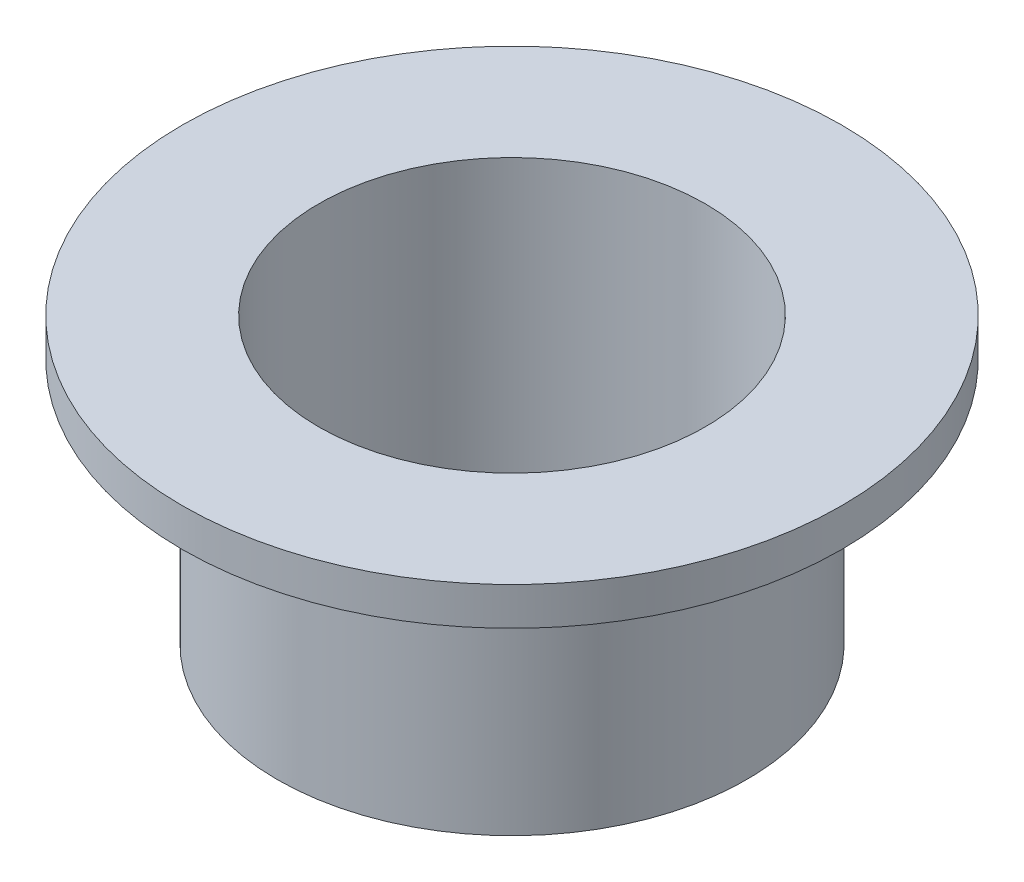
SolidWorks part; units mm, degrees
ref_plane "Front Plane" through (0, 0, 0) normal (0, 0, 1) x (1, 0, 0)
ref_plane "Top Plane" through (0, 0, 0) normal (0, 1, 0) x (1, 0, 0)
ref_plane "Right Plane" through (0, 0, 0) normal (1, 0, 0) x (0, 0, -1)
sketch "Sketch1" plane through (0, 0, 0) normal (0, 0, 1) x (1, 0, 0)
  line L0 (0, 0) -> (0, 17306.5647) construction
  line L1 (10.1875, -15) -> (12.375, -15)
  line L2 (12.375, -15) -> (12.375, -2)
  line L3 (12.375, -2) -> (17.375, -2)
  line L4 (17.375, -2) -> (17.375, 0)
  line L5 (17.375, 0) -> (10.1875, 0)
  line L6 (10.1875, 0) -> (10.1875, -15)
  dimension "D1" = 20.375
  dimension "D2" = 24.75
  dimension "D3" = 5
  dimension "D4" = 15
  dimension "D5" = 2
revolve "Revolve1" add sketch "Sketch1" angle 360 about L0
